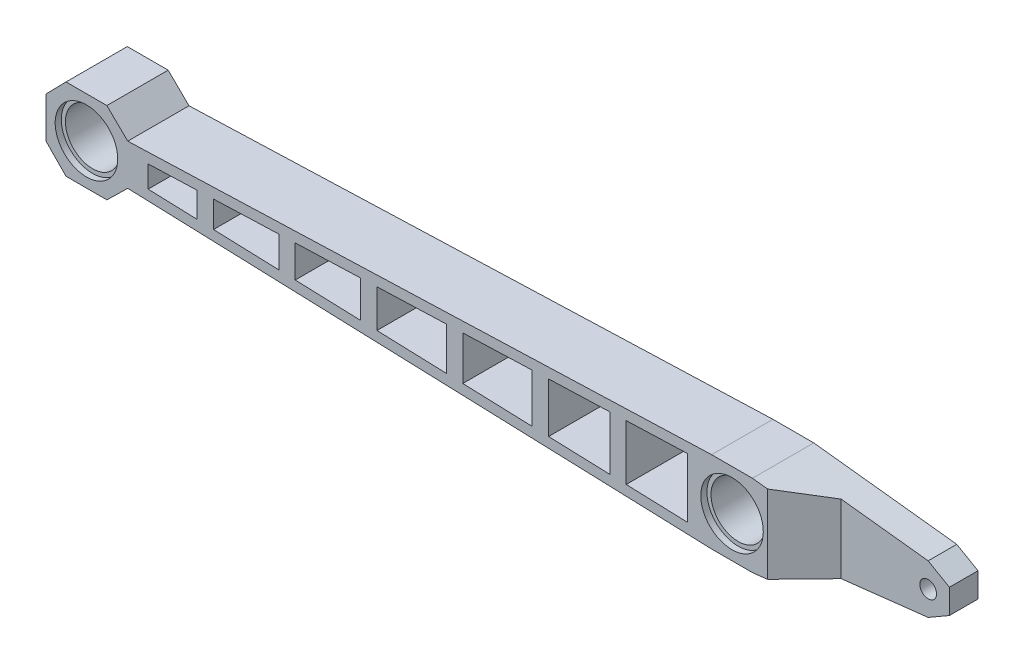
SolidWorks part; units mm, degrees
ref_plane "前视基准面" through (0, 0, 0) normal (0, 0, 1) x (1, 0, 0)
ref_plane "上视基准面" through (0, 0, 0) normal (0, 1, 0) x (1, 0, 0)
ref_plane "右视基准面" through (0, 0, 0) normal (1, 0, 0) x (0, 0, -1)
sketch "草图1" plane through (0, 0, 0) normal (0, 0, 1) x (1, 0, 0)
  line L9 (198, 6) -> (203.1962, 3)
  line L10 (203.1962, 3) -> (203.1962, -3)
  line L11 (203.1962, -3) -> (198, -6)
  line L13 (0, 0) -> (175.5117, 0) construction
  line L15 (10.101, 5) -> (153, 10)
  line L16 (153, 10) -> (163, 10)
  line L17 (163, 10) -> (198, 6)
  line L18 (163, -10) -> (198, -6)
  line L19 (153, -10) -> (163, -10)
  line L20 (10.101, -5) -> (153, -10)
  line L27 (10.101, 5) -> (5, 10)
  line L28 (5, 10) -> (-5, 10)
  line L29 (-5, 10) -> (-9.899, 5)
  line L30 (0, 0) -> (-16.3337, 0) construction
  line L31 (-9.899, 5) -> (-9.899, -5)
  line L32 (0, 10) -> (0, -6) construction
  line L33 (10.101, -5) -> (5, -10)
  line L34 (5, -10) -> (-5, -10)
  line L35 (-5, -10) -> (-9.899, -5)
  line L36 (158, 10) -> (158, -8.71) construction
  line L37 (15.101, -2.6734) -> (15.101, 2.6734)
  line L38 (15.101, 2.6734) -> (27.101, 3.0933)
  line L39 (27.101, 3.0933) -> (27.101, -3.0933)
  line L40 (31.101, -3.2333) -> (31.101, 3.2333)
  line L41 (31.101, 3.2333) -> (47.101, 3.7931)
  line L42 (47.101, 3.7931) -> (47.101, -3.7931)
  line L43 (51.101, -3.933) -> (51.101, 3.933)
  line L44 (51.101, 3.933) -> (67.101, 4.4929)
  line L45 (67.101, 4.4929) -> (67.101, -4.4929)
  line L46 (71.101, 4.6328) -> (88.101, 5.2277)
  line L47 (109.101, 5.9625) -> (109.101, -5.9625)
  line L48 (71.101, 4.6328) -> (71.101, -4.6328)
  line L49 (88.101, 5.2277) -> (88.101, -5.2277)
  line L50 (92.101, 5.3676) -> (92.101, -5.3676)
  line L51 (92.101, 5.3676) -> (109.101, 5.9625)
  line L52 (71.101, -4.6328) -> (88.101, -5.2277)
  line L53 (92.101, -5.3676) -> (109.101, -5.9625)
  line L54 (51.101, -3.933) -> (67.101, -4.4929)
  line L55 (31.101, -3.2333) -> (47.101, -3.7931)
  line L56 (15.101, -2.6734) -> (27.101, -3.0933)
  line L57 (113.101, -6.1024) -> (128.101, -6.6273)
  line L58 (147.101, -7.2921) -> (147.101, 7.2921)
  line L59 (147.101, 7.2921) -> (132.101, 6.7672)
  line L60 (113.101, 6.1024) -> (113.101, -6.1024)
  line L61 (128.101, 6.6273) -> (128.101, -6.6273)
  line L62 (132.101, 6.7672) -> (132.101, -6.7672)
  line L63 (128.101, 6.6273) -> (113.101, 6.1024)
  line L64 (132.101, -6.7672) -> (147.101, -7.2921)
  circle A1 centre (0, 0) radius 6.65
  circle A2 centre (198, 0) radius 2.05
  circle A3 centre (158, 0) radius 6.65
  point P29 (-9.899, 0)
  point P51 (71.101, 0)
  point P52 (88.101, 0)
  point P53 (92.101, 0)
  point P54 (109.101, 0)
  point P55 (67.101, 0)
  point P56 (51.101, 0)
  point P57 (47.101, 0)
  point P58 (31.101, 0)
  point P59 (27.101, 0)
  point P60 (15.101, 0)
  dimension "D1" = 5
  dimension "D5" = 158
  dimension "D6" = 40
  dimension "D7" = 13.3
  dimension "D14" = 4.1
  dimension "D15" = 13.3
  dimension "D2" = 7
  dimension "D3" = 6
  dimension "D4" = 12
  dimension "D8" = 10
  dimension "D9" = 10
  dimension "D10" = 20
  dimension "D11" = 10
  dimension "D12" = 20
  dimension "D13" = 10
  dimension "D16" = 5
  dimension "D17" = 12
  dimension "D18" = 2.5
  dimension "D19" = 2.5
  dimension "D20" = 16
  dimension "D21" = 4
  dimension "D22" = 2.5
  dimension "D23" = 4
  dimension "D24" = 16
  dimension "D25" = 4
  dimension "D26" = 4
  dimension "D27" = 17
  dimension "D28" = 17
  dimension "D29" = 2.5
  dimension "D30" = 4
  dimension "D31" = 4
  dimension "D32" = 15
  dimension "D33" = 15
extrude "凸台-拉伸1" add sketch "草图1" along normal blind 15
sketch "草图2" plane through (0, -10, 0) normal (0, -1, 0) x (1, 0, 0)
  line L0 (166.7, 15) -> (176.6962, 7)
  line L1 (163, 15) -> (198, 15) construction
  line L2 (176.6962, 7) -> (203.1962, 7)
  line L3 (203.1962, 15) -> (203.1962, 0) construction
  line L4 (203.1962, 7) -> (203.1962, 15)
  line L5 (203.1962, 15) -> (166.7, 15)
  line L6 (163, 0) -> (198, 0) construction
  line L7 (163, 15) -> (163, 0) construction
  dimension "D1" = 7
  dimension "D2" = 3.7
  dimension "D3" = 26.5
extrude "切除-拉伸1" cut sketch "草图2" against normal through all
sketch "草图3" plane through (0, 0, 15) normal (0, 0, 1) x (1, 0, 0)
  circle A0 centre (0, 0) radius 7.65
  circle A1 centre (158, 0) radius 7.65
  dimension "D1" = 15.3
extrude "切除-拉伸2" cut sketch "草图3" against normal blind 1.5
sketch "草图4" plane through (0, 0, 0) normal (0, 0, -1) x (-1, 0, 0)
  circle A0 centre (-158, 0) radius 7.65
  circle A1 centre (0, 0) radius 7.65
  dimension "D1" = 15.3
extrude "切除-拉伸3" cut sketch "草图4" against normal blind 1.5
